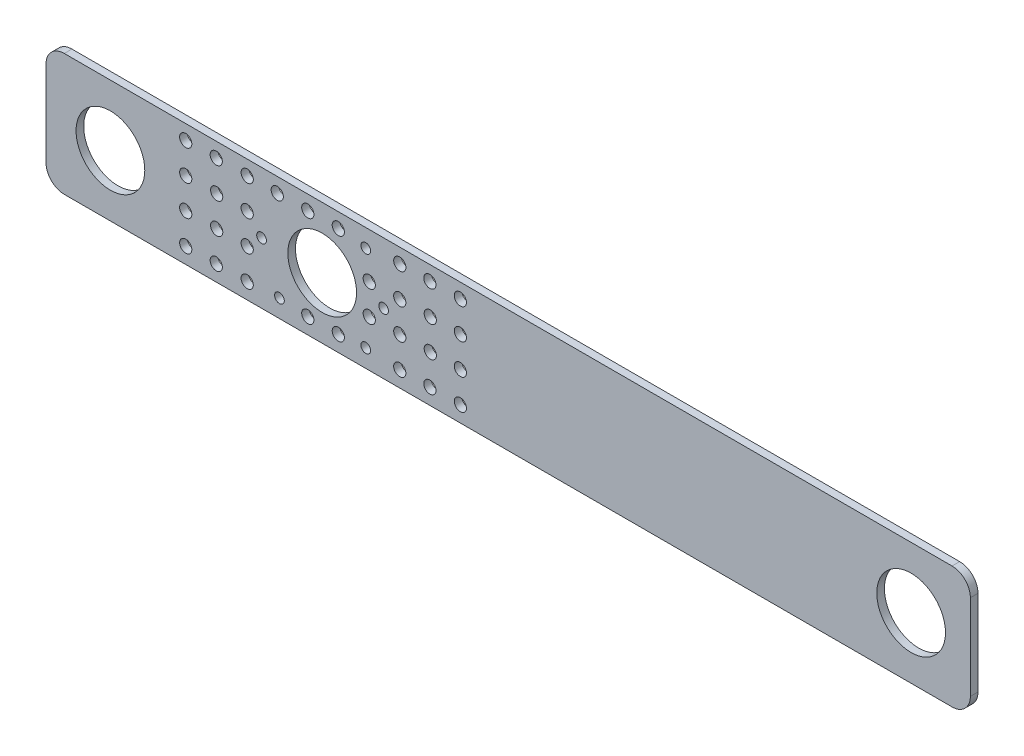
SolidWorks part; units mm, degrees
ref_plane "Front Plane" through (0, 0, 0) normal (0, 0, 1) x (1, 0, 0)
ref_plane "Top Plane" through (0, 0, 0) normal (0, 1, 0) x (1, 0, 0)
ref_plane "Right Plane" through (0, 0, 0) normal (1, 0, 0) x (0, 0, -1)
sketch "Sketch1" plane through (0, 0, 0) normal (0, 0, 1) x (1, 0, 0)
  line L1 (-100.9194, 26.073) -> (283.7947, 26.073)
  line L2 (-100.9194, 26.073) -> (-100.9194, -24.727)
  line L3 (-100.9194, -24.727) -> (283.7947, -24.727)
  line L4 (283.7947, 26.073) -> (283.7947, -24.727)
  circle A0 centre (-74.1099, 0.673) radius 14.3002
  circle A1 centre (14.0281, 0.673) radius 14.3002
  circle A2 centre (259.1381, 0.673) radius 14.3002
  circle A4 centre (39.5921, 0.663) radius 2.0193
  circle A5 centre (32.1526, -17.2976) radius 2.0193
  circle A6 centre (-3.7684, -17.2976) radius 2.0193
  circle A7 centre (32.1526, 18.6235) radius 2.0193
  circle A8 centre (-11.2079, 0.663) radius 2.0193
  circle A9 centre (-29.8855, 7.2896) radius 2.54 construction
  circle A10 centre (-29.8855, -5.4104) radius 2.54 construction
  circle A11 centre (-17.1855, 7.2896) radius 2.54 construction
  circle A12 centre (-17.1855, -5.4104) radius 2.54 construction
  circle A13 centre (-17.1855, -18.1104) radius 2.54 construction
  circle A14 centre (-17.1855, 19.9896) radius 2.54 construction
  circle A15 centre (-30.0668, 19.9896) radius 2.54 construction
  circle A16 centre (33.6145, -5.4104) radius 2.54 construction
  circle A17 centre (33.6145, 7.2896) radius 2.54 construction
  circle A18 centre (59.0145, -5.4104) radius 2.54 construction
  circle A19 centre (59.0145, 7.2896) radius 2.54 construction
  circle A20 centre (46.3145, 7.2896) radius 2.54 construction
  circle A21 centre (46.3145, -5.4104) radius 2.54 construction
  circle A22 centre (46.3145, -18.1104) radius 2.54 construction
  circle A23 centre (58.8332, -18.1104) radius 2.54 construction
  circle A24 centre (71.5332, -18.1104) radius 2.54 construction
  circle A25 centre (71.5332, -5.4104) radius 2.54 construction
  circle A26 centre (71.5332, 7.2896) radius 2.54 construction
  circle A27 centre (71.5332, 19.9896) radius 2.54 construction
  circle A28 centre (58.8332, 19.9896) radius 2.54 construction
  circle A29 centre (46.3145, 19.9896) radius 2.54 construction
  circle A30 centre (20.7332, 19.9896) radius 2.54 construction
  circle A31 centre (8.0332, 19.9896) radius 2.54 construction
  circle A32 centre (-4.6668, 19.9896) radius 2.54 construction
  circle A33 centre (20.7332, -18.1104) radius 2.54 construction
  circle A34 centre (8.0332, -18.1104) radius 2.54 construction
  circle A35 centre (-30.0668, -18.1104) radius 2.54 construction
  circle A36 centre (-42.7668, -18.1104) radius 2.54 construction
  circle A37 centre (-42.7668, 19.9896) radius 2.54 construction
  circle A38 centre (-42.7668, 7.2896) radius 2.54 construction
  circle A39 centre (-42.7668, -5.4104) radius 2.54 construction
  circle A40 centre (-29.8855, 7.2896) radius 2.54
  circle A41 centre (-29.8855, -5.4104) radius 2.54
  circle A42 centre (-17.1855, 7.2896) radius 2.54
  circle A43 centre (-17.1855, -5.4104) radius 2.54
  circle A44 centre (-17.1855, -18.1104) radius 2.54
  circle A45 centre (-17.1855, 19.9896) radius 2.54
  circle A46 centre (-30.0668, 19.9896) radius 2.54
  circle A47 centre (33.6145, -5.4104) radius 2.54
  circle A48 centre (33.6145, 7.2896) radius 2.54
  circle A49 centre (59.0145, -5.4104) radius 2.54
  circle A50 centre (59.0145, 7.2896) radius 2.54
  circle A51 centre (46.3145, 7.2896) radius 2.54
  circle A52 centre (46.3145, -5.4104) radius 2.54
  circle A53 centre (46.3145, -18.1104) radius 2.54
  circle A54 centre (58.8332, -18.1104) radius 2.54
  circle A55 centre (71.5332, -18.1104) radius 2.54
  circle A56 centre (71.5332, -5.4104) radius 2.54
  circle A57 centre (71.5332, 7.2896) radius 2.54
  circle A58 centre (71.5332, 19.9896) radius 2.54
  circle A59 centre (58.8332, 19.9896) radius 2.54
  circle A60 centre (46.3145, 19.9896) radius 2.54
  circle A61 centre (20.7332, 19.9896) radius 2.54
  circle A62 centre (8.0332, 19.9896) radius 2.54
  circle A63 centre (-4.6668, 19.9896) radius 2.54
  circle A64 centre (20.7332, -18.1104) radius 2.54
  circle A65 centre (8.0332, -18.1104) radius 2.54
  circle A66 centre (-30.0668, -18.1104) radius 2.54
  circle A67 centre (-42.7668, -18.1104) radius 2.54
  circle A68 centre (-42.7668, 19.9896) radius 2.54
  circle A69 centre (-42.7668, 7.2896) radius 2.54
  circle A70 centre (-42.7668, -5.4104) radius 2.54
  dimension "D3" = 88.138
  dimension "D1" = 50.8
  dimension "D2" = 25.4
  dimension "D4" = 245.11
  dimension "D5" = 25.4
  dimension "D6" = 25.4
extrude "Boss-Extrude1" add sketch "Sketch1" along normal blind 3.175
fillet "Fillet1" radius 7.62 4 edges at (283.7947, -24.727, 1.5875) (283.7947, 26.073, 1.5875) (-100.9194, -24.727, 1.5875) (-100.9194, 26.073, 1.5875)
